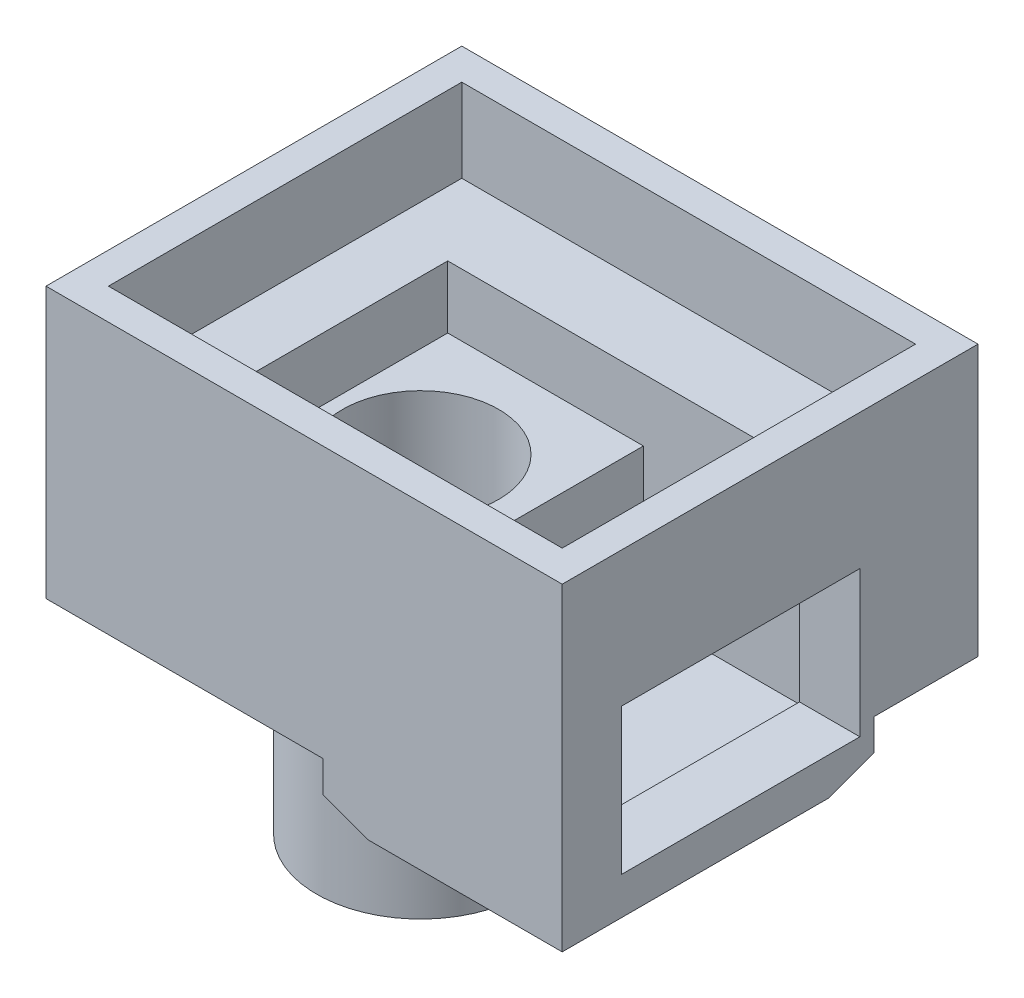
SolidWorks part; units mm, degrees
ref_plane "Front Plane" through (0, 0, 0) normal (0, 0, 1) x (1, 0, 0)
ref_plane "Top Plane" through (0, 0, 0) normal (0, 1, 0) x (1, 0, 0)
ref_plane "Right Plane" through (0, 0, 0) normal (1, 0, 0) x (0, 0, -1)
sketch "Sketch1" plane through (0, 0, 0) normal (0, 1, 0) x (1, 0, 0)
  line L0 (-0.5, 4.9749) -> (-0.5, 7)
  line L1 (-0.5, 7) -> (0.5, 7)
  line L2 (0.5, 7) -> (0.5, 4.9749)
  circle A0 centre (0, 0) radius 5
  circle A1 centre (0, 0) radius 2.5
  point P8 (0, 7)
  dimension "D1" = 10
  dimension "D2" = 5
  dimension "D3" = 1
  dimension "D4" = 7
extrude "Boss-Extrude1" add sketch "Sketch1" along normal blind 15.8 contours A0 L2 L1 L0 | A0 A1
sketch "Sketch2" plane through (0, 15.8, 0) normal (0, 1, 0) x (1, 0, 0)
  circle A0 centre (0, 0) radius 3.75
  dimension "D2" = 7.5
extrude "Cut-Extrude1" cut sketch "Sketch2" against normal blind 13
sketch "Sketch4" plane through (0.5, 0, 0) normal (1, 0, 0) x (0, 0, -1)
  line L0 (4.9749, 15.8) -> (4.9749, 0) construction
  line L1 (7, 0) -> (4.9749, 0)
  line L2 (7, 0) -> (7, 2.5)
  line L3 (7, 2.5) -> (4.9749, 2.5)
  line L4 (4.9749, 0) -> (4.9749, 2.5)
  dimension "D1" = 2.5
extrude "Cut-Extrude2" cut sketch "Sketch4" against normal through all
sketch "Sketch10" plane through (0.5, 0, 0) normal (1, 0, 0) x (0, 0, -1)
  line L1 (4.9749, 15.8) -> (9.9749, 15.8)
  line L2 (4.9749, 15.8) -> (4.9749, 9.8)
  line L3 (4.9749, 9.8) -> (9.9749, 9.8)
  line L4 (9.9749, 15.8) -> (9.9749, 9.8)
  dimension "D1" = 6
  dimension "D2" = 5
extrude "Boss-Extrude3" add sketch "Sketch10" against normal up to surface (1 mm away) up to face at (-0.5, 9.15, -5.9875)
sketch "Sketch12" plane through (0, 15.8, 0) normal (0, 1, 0) x (1, 0, 0)
  line L0 (-3.75, -3.3072) -> (-3.75, 3.3072)
  arc A1 (-0.5, 4.9749) -> (0.5, 4.9749) centre (0, 0) ccw construction
  circle A2 centre (0, 0) radius 3.75 construction
  arc A3 (-3.75, -3.3072) -> (-3.75, 3.3072) centre (0, 0) cw
extrude "Boss-Extrude4" add sketch "Sketch12" along normal blind 1
sketch "Sketch13" plane through (0, 9.8, 0) normal (0, -1, 0) x (1, 0, 0)
  line L3 (-0.5, -9.9749) -> (0.5, -9.9749) construction
  line L4 (-8, 8) -> (14.8, 8)
  line L5 (-8, 8) -> (-8, -9.9749)
  line L6 (-8, -9.9749) -> (14.8, -9.9749)
  line L7 (14.8, 8) -> (14.8, -9.9749)
  circle A0 centre (0, 0) radius 5
  dimension "D4" = 10
  dimension "D1" = 22.8
  dimension "D2" = 8
  dimension "D3" = 8
extrude "Boss-Extrude7" add sketch "Sketch13" against normal offset from surface (10 mm away) 4 up to face at (-0.6668, 15.8, -2.9176) offset beyond the face yes
sketch "Sketch14" plane through (0, 19.8, 0) normal (0, 1, 0) x (1, 0, 0)
  line L0 (-4.4, 5.7) -> (10.3, 5.7)
  line L1 (-3.9, 5.2) -> (10.3, 5.2) construction
  line L2 (-3.9, 5.2) -> (-3.9, -6.75) construction
  line L3 (-3.9, -6.75) -> (10.3, -6.75) construction
  line L4 (10.3, 5.2) -> (10.3, -6.75) construction
  line L5 (10.3, 5.2) -> (12.4, 5.2) construction
  line L6 (10.3, 5.2) -> (10.3, -6.75) construction
  line L7 (10.3, -6.75) -> (12.4, -6.75) construction
  line L8 (12.4, 5.2) -> (12.4, -6.75) construction
  line L9 (10.3, 5.7) -> (12.9, 5.7)
  line L10 (12.9, 5.7) -> (12.9, -7.25)
  line L11 (10.3, -7.25) -> (12.9, -7.25)
  line L12 (-4.4, -7.25) -> (10.3, -7.25)
  line L13 (-4.4, 5.7) -> (-4.4, -7.25)
  point P8 (0, 0)
  dimension "D1" = 6.75
  dimension "D2" = 14.2
  dimension "D3" = 3.9
  dimension "D4" = 5.2
  dimension "D5" = 2.1
  dimension "D6" = 0.5
extrude "Cut-Extrude3" cut sketch "Sketch14" against normal up to surface (4 mm away)
sketch "Sketch15" plane through (0, 19.8, 0) normal (0, 1, 0) x (1, 0, 0)
  line L8 (-7.5, 9.4749) -> (-7.5, -7.5)
  line L9 (-7.5, -7.5) -> (14.3, -7.5)
  line L10 (14.3, -7.5) -> (14.3, 9.4749)
  line L11 (14.3, 9.4749) -> (-7.5, 9.4749)
  line L12 (-7.5, 9.4749) -> (-7.5, -7.5)
  line L13 (-7.5, -7.5) -> (14.3, -7.5)
  line L14 (14.3, -7.5) -> (14.3, 9.4749)
  line L15 (14.3, 9.4749) -> (-7.5, 9.4749)
  dimension "D1" = 0.5
extrude "Cut-Extrude4" cut sketch "Sketch15" against normal blind 1
sketch "Sketch17" plane through (0, 9.8, 0) normal (0, -1, 0) x (1, 0, 0)
  line L0 (14.8, -9.9749) -> (14.8, 8) construction
  line L1 (14.8, -5.9749) -> (4.3, -5.9749)
  line L2 (14.8, -5.9749) -> (14.8, 8)
  line L3 (14.8, 8) -> (4.3, 8)
  line L4 (4.3, -5.9749) -> (4.3, 8)
  line L5 (14.8, 8) -> (-8, 8) construction
  arc A1 (0.5, -4.9749) -> (-0.5, -4.9749) centre (0, 0) ccw construction
  dimension "D1" = 1
  dimension "D2" = 4.3
extrude "Boss-Extrude9" add sketch "Sketch17" along normal blind 3
sketch "Sketch16" plane through (0, 15.8, 0) normal (0, 1, 0) x (1, 0, 0)
  line L1 (12.9, 5.7) -> (5, 5.7)
  line L2 (12.9, 5.7) -> (12.9, -7.25)
  line L3 (12.9, -7.25) -> (5, -7.25)
  line L4 (5, 5.7) -> (5, -7.25)
  line L5 (12.9, -7.25) -> (-4.4, -7.25) construction
  circle A1 centre (0, 0) radius 3.75 construction
  point P5 (3.75, -6.9729)
  dimension "D1" = 5
extrude "Cut-Extrude6" cut sketch "Sketch16" against normal blind 7
sketch "Sketch19" plane through (0, 19.8, 0) normal (0, 1, 0) x (1, 0, 0)
  line L0 (-7.5, -7.5) -> (14.3, -7.5) construction
  line L1 (14.3, -7.5) -> (14.3, 9.4749) construction
  line L2 (-7.5, 9.4749) -> (-7.5, -7.5) construction
  line L3 (14.3, 9.4749) -> (-7.5, 9.4749) construction
  line L4 (-8, 9.9749) -> (-8, -8)
  line L5 (-8, -8) -> (14.8, -8)
  line L6 (14.8, -8) -> (14.8, 9.9749)
  line L7 (14.8, 9.9749) -> (-8, 9.9749)
  line L8 (-8, 9.9749) -> (-8, -8)
  line L9 (-8, -8) -> (14.8, -8)
  line L10 (14.8, -8) -> (14.8, 9.9749)
  line L11 (14.8, 9.9749) -> (-8, 9.9749)
  line L12 (-7.5, -7.5) -> (14.3, -7.5)
  line L13 (14.3, -7.5) -> (14.3, 9.4749)
  line L14 (-7.5, 9.4749) -> (-7.5, -7.5)
  line L15 (14.3, 9.4749) -> (-7.5, 9.4749)
  dimension "D1" = 0
extrude "Boss-Extrude10" add sketch "Sketch19" along normal blind 3
sketch "Sketch20" plane through (0, 16.8, 0) normal (0, 1, 0) x (1, 0, 0)
  line L1 (-4.4, -2.3749) -> (-4.4, 2.3749)
  line L2 (-4.4, -2.3749) -> (-4.4, 2.3749)
  arc A1 (-4.4, 2.3749) -> (-4.4, -2.3749) centre (0, 0) ccw
  arc A2 (-4.4, 2.3749) -> (-4.4, -2.3749) centre (0, 0) ccw
  dimension "D1" = 0
extrude "Boss-Extrude11" add sketch "Sketch20" along normal up to surface (2 mm away) up to face at (3.4, 18.8, -0.9875)
sketch "Sketch21" plane through (0, 0, 7.25) normal (0, 0, -1) x (-1, 0, 0)
  line L6 (4.4, 18.8) -> (-12.9, 18.8)
  line L7 (-12.9, 18.8) -> (-12.9, 8.8)
  line L8 (-12.9, 8.8) -> (-5, 8.8)
  line L9 (-5, 8.8) -> (-5, 15.8)
  line L10 (-5, 15.8) -> (4.4, 15.8)
  line L11 (4.4, 15.8) -> (4.4, 18.8)
  line L12 (4.4, 18.8) -> (-12.9, 18.8)
  line L13 (-12.9, 18.8) -> (-12.9, 8.8)
  line L14 (-12.9, 8.8) -> (-5, 8.8)
  line L15 (-5, 8.8) -> (-5, 15.8)
  line L16 (-5, 15.8) -> (4.4, 15.8)
  line L17 (4.4, 15.8) -> (4.4, 18.8)
  dimension "D1" = 0
extrude "Cut-Extrude7" cut sketch "Sketch21" against normal up to surface (0.25 mm away) up to face at (3.4, 20.8, 7.5)
sketch "Sketch22" plane through (0, 0, 8) normal (0, 0, 1) x (1, 0, 0)
  line L6 (14.8, 6.8) -> (14.8, 22.8)
  line L7 (14.8, 22.8) -> (-8, 22.8)
  line L8 (-8, 22.8) -> (-8, 9.8)
  line L9 (-8, 9.8) -> (4.3, 9.8)
  line L10 (4.3, 9.8) -> (4.3, 6.8)
  line L11 (4.3, 6.8) -> (14.8, 6.8)
  line L12 (14.8, 6.8) -> (14.8, 22.8)
  line L13 (14.8, 22.8) -> (-8, 22.8)
  line L14 (-8, 22.8) -> (-8, 9.8)
  line L15 (-8, 9.8) -> (4.3, 9.8)
  line L16 (4.3, 9.8) -> (4.3, 6.8)
  line L17 (4.3, 6.8) -> (14.8, 6.8)
  dimension "D1" = 0
extrude "Boss-Extrude12" add sketch "Sketch22" along normal blind 1
sketch "Sketch23" plane through (-8, 0, 0) normal (-1, 0, 0) x (0, 0, 1)
  line L4 (-9.9749, 9.8) -> (9, 9.8)
  line L5 (9, 9.8) -> (9, 22.8)
  line L6 (9, 22.8) -> (-9.9749, 22.8)
  line L7 (-9.9749, 22.8) -> (-9.9749, 9.8)
  line L8 (-9.9749, 9.8) -> (9, 9.8)
  line L9 (9, 9.8) -> (9, 22.8)
  line L10 (9, 22.8) -> (-9.9749, 22.8)
  line L11 (-9.9749, 22.8) -> (-9.9749, 9.8)
  dimension "D1" = 0
extrude "Boss-Extrude13" add sketch "Sketch23" along normal blind 1
sketch "Sketch24" plane through (0, 0, -9.9749) normal (0, 0, -1) x (-1, 0, 0)
  line L4 (-14.8, 9.8) -> (9, 9.8)
  line L5 (9, 9.8) -> (9, 22.8)
  line L6 (9, 22.8) -> (-14.8, 22.8)
  line L7 (-14.8, 22.8) -> (-14.8, 9.8)
  line L8 (-14.8, 9.8) -> (9, 9.8)
  line L9 (9, 9.8) -> (9, 22.8)
  line L10 (9, 22.8) -> (-14.8, 22.8)
  line L11 (-14.8, 22.8) -> (-14.8, 9.8)
  dimension "D1" = 0
extrude "Boss-Extrude14" add sketch "Sketch24" along normal blind 1
sketch "Sketch25" plane through (14.8, 0, 0) normal (1, 0, 0) x (0, 0, -1)
  line L6 (5.9749, 9.8) -> (10.9749, 9.8)
  line L7 (10.9749, 9.8) -> (10.9749, 22.8)
  line L8 (10.9749, 22.8) -> (-9, 22.8)
  line L9 (-9, 22.8) -> (-9, 6.8)
  line L10 (-9, 6.8) -> (5.9749, 6.8)
  line L11 (5.9749, 6.8) -> (5.9749, 9.8)
  line L12 (5.9749, 9.8) -> (10.9749, 9.8)
  line L13 (10.9749, 9.8) -> (10.9749, 22.8)
  line L14 (10.9749, 22.8) -> (-9, 22.8)
  line L15 (-9, 22.8) -> (-9, 6.8)
  line L16 (-9, 6.8) -> (5.9749, 6.8)
  line L17 (5.9749, 6.8) -> (5.9749, 9.8)
  dimension "D1" = 0
extrude "Boss-Extrude15" add sketch "Sketch25" along normal blind 1
sketch "Sketch26" plane through (12.9, 0, 0) normal (-1, 0, 0) x (0, 0, 1)
  line L0 (-5.3, 16.3) -> (-5.3, 9.3)
  line L5 (-4.8, 15.8) -> (5.65, 15.8) construction
  line L6 (-4.8, 15.8) -> (-4.8, 9.8) construction
  line L7 (-4.8, 9.8) -> (5.65, 9.8) construction
  line L8 (5.65, 15.8) -> (5.65, 9.8) construction
  line L9 (-5.3, 9.3) -> (6.15, 9.3)
  line L10 (6.15, 16.3) -> (6.15, 9.3)
  line L11 (-5.3, 16.3) -> (6.15, 16.3)
  dimension "D1" = 0.5
extrude "Cut-Extrude8" cut sketch "Sketch26" against normal through all contours L11 L0 L9 L10 | L6 L5 L8 L7
sketch "Sketch28" plane through (0, 6.8, 0) normal (0, -1, 0) x (1, 0, 0)
  line L5 (4.3, -2.5515) -> (4.3, -5.9749)
  line L6 (4.3, -5.9749) -> (15.8, -5.9749)
  line L7 (15.8, -5.9749) -> (15.8, 9)
  line L8 (15.8, 9) -> (4.3, 9)
  line L9 (4.3, 9) -> (4.3, 2.5515)
  line L10 (4.3, -2.5515) -> (4.3, -5.9749)
  line L11 (4.3, -5.9749) -> (15.8, -5.9749)
  line L12 (15.8, -5.9749) -> (15.8, 9)
  line L13 (15.8, 9) -> (4.3, 9)
  line L14 (4.3, 9) -> (4.3, 2.5515)
  arc A1 (4.3, -2.5515) -> (4.3, 2.5515) centre (0, 0) ccw
  arc A2 (4.3, -2.5515) -> (4.3, 2.5515) centre (0, 0) ccw
  dimension "D1" = 0
extrude "Cut-Extrude10" cut sketch "Sketch28" against normal blind 0.7
chamfer "Chamfer4" distance 0.8 angle 70 2 edges at (10.05, 7.5, -5.9749) (4.3, 7.5, -4.2632)
